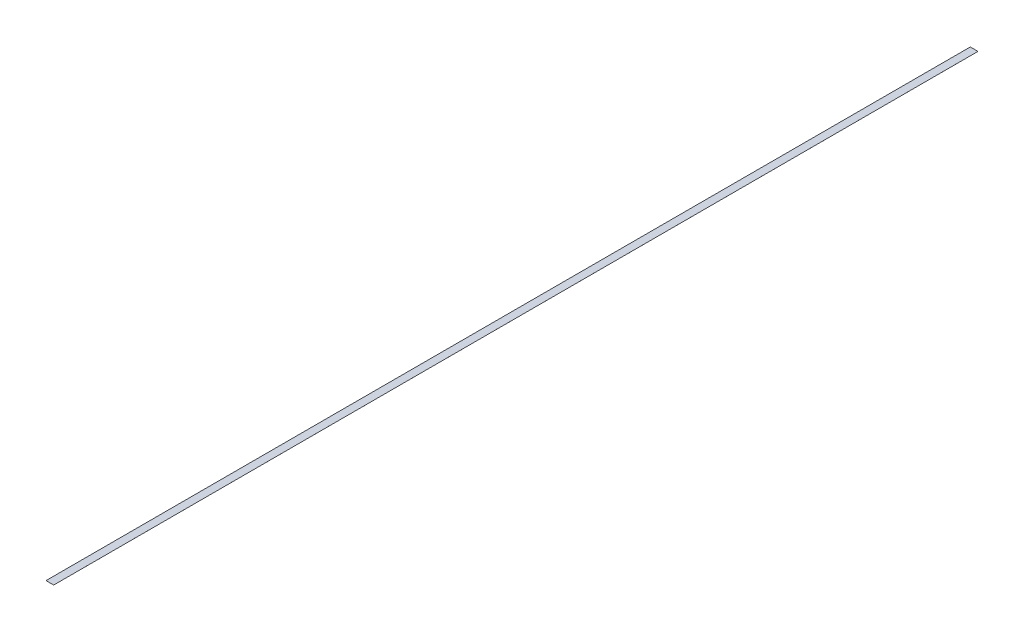
SolidWorks part; units mm, degrees
ref_plane "Front Plane" through (0, 0, 0) normal (0, 0, 1) x (1, 0, 0)
ref_plane "Top Plane" through (0, 0, 0) normal (0, 1, 0) x (1, 0, 0)
ref_plane "Right Plane" through (0, 0, 0) normal (1, 0, 0) x (0, 0, -1)
sketch "Sketch1" plane through (0, 0, 0) normal (0, 0, 1) x (1, 0, 0)
  line L0 (-12.7, 0) -> (12.7, 0) construction
  line L1 (0, -0.0127) -> (0, 0.0127) construction
  line L5 (-12.7, 0.0127) -> (12.7, 0.0127) construction
  line L7 (-12.7, 0.0127) -> (-12.7, -0.0127) construction
  line L8 (12.7, -0.0127) -> (12.7, 0.0127) construction
  line L13 (-12.7, -0.0127) -> (12.7, -0.0127) construction
  point P0 (0, 0)
  point P4 (0, 0)
  point P9 (0, 0)
  point P22 (0, 0.0127)
  dimension "Thickness" = 0.0254
  dimension "D1" = 25.4
sketch "Sketch2" plane through (0, 0, 0) normal (0, 1, 0) x (0, 0, -1)
  line L0 (1524, 0) -> (-1524, 0) construction
  line L2 (-1524, 12.7) -> (1524, 12.7) construction
  line L3 (-1524, 12.7) -> (-1524, -12.7) construction
  line L4 (-1524, -12.7) -> (1524, -12.7) construction
  line L5 (1524, 12.7) -> (1524, -12.7) construction
  line L6 (-1524, 12.7) -> (1524, -12.7) construction
  line L7 (-1524, -12.7) -> (1524, 12.7) construction
  point P4 (0, 0)
  point P7 (0, 0)
  point P12 (-1422.4, 12.7)
  point P13 (1422.4, 12.7)
  dimension "Length" = 3048
  dimension "Width" = 25.4
  dimension "D1" = 101.6
  dimension "D2" = 101.6
sketch "Sketch3" plane through (0, 0, 0) normal (0, 0, 1) x (1, 0, 0)
  line L3 (-12.7, 0.0127) -> (12.7, 0.0127)
  line L17 (12.7, 0.0127) -> (12.7, -0.0127)
  line L18 (12.7, -0.0127) -> (-12.7, -0.0127)
  line L19 (-12.7, -0.0127) -> (-12.7, 0.0127)
extrude "Boss-Extrude1" add sketch "Sketch3" along normal mid plane 3048
equation "\"D1@Boss-Extrude1\" = \"Length@Sketch2\""
equation "\"D1@Sketch1\"=\"Width@Sketch2\""
equation "\"D1@Sketch2\"=\"Width@Sketch2\"*4"
equation "\"D2@Sketch2\"=\"D1@Sketch2\""
